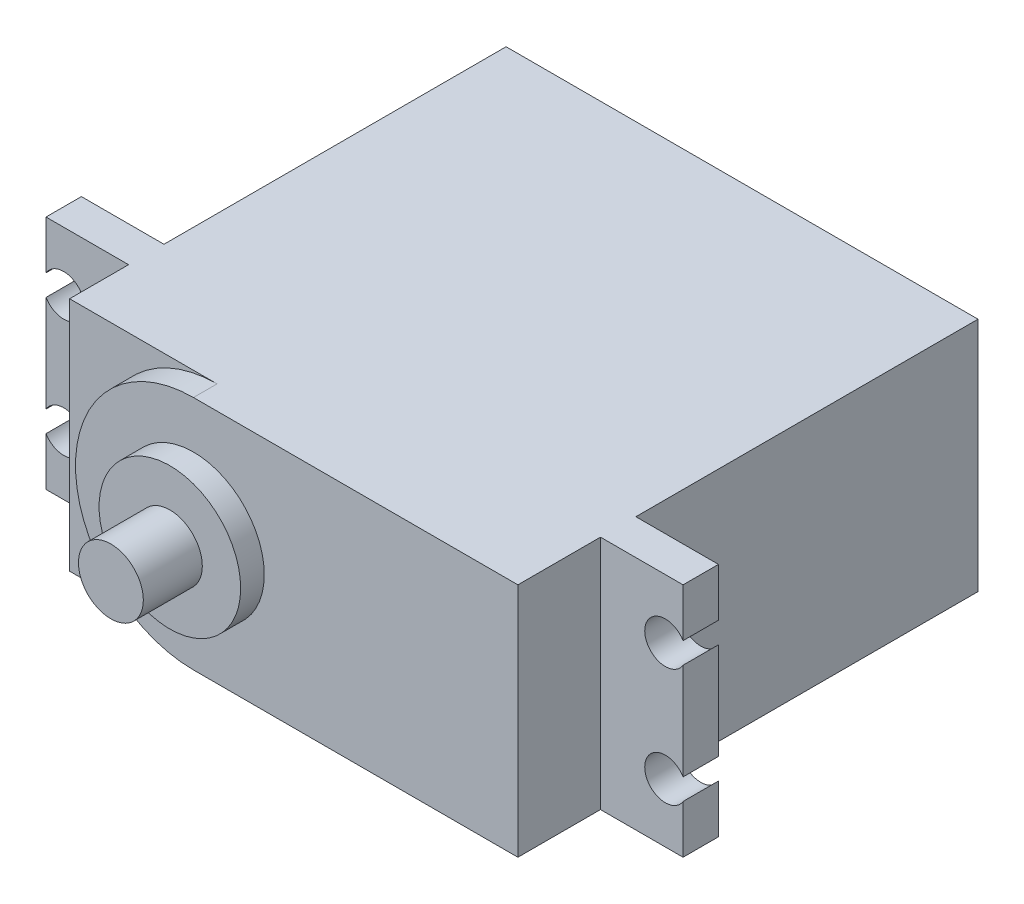
SolidWorks part; units mm, degrees
ref_plane "Front Plane" through (0, 0, 0) normal (0, 0, 1) x (1, 0, 0)
ref_plane "Top Plane" through (0, 0, 0) normal (0, 1, 0) x (1, 0, 0)
ref_plane "Right Plane" through (0, 0, 0) normal (1, 0, 0) x (0, 0, -1)
sketch "Sketch1" plane through (0, 0, 0) normal (0, 0, 1) x (1, 0, 0)
  line L1 (-20, -10) -> (20, -10)
  line L2 (-20, -10) -> (-20, 10)
  line L3 (-20, 10) -> (20, 10)
  line L4 (20, -10) -> (20, 10)
  line L5 (-20, -10) -> (20, 10) construction
  line L6 (-20, 10) -> (20, -10) construction
  point P0 (0, 0)
  dimension "D1" = 40
  dimension "D2" = 20
extrude "Boss-Extrude1" add sketch "Sketch1" along normal blind 37
sketch "Sketch2" plane through (0, 0, 37) normal (0, 0, 1) x (1, 0, 0)
  line L0 (-20, 10) -> (-20, -10) construction
  line L1 (-7.5, 10) -> (20, 10)
  line L2 (20, 10) -> (20, -10)
  line L3 (20, -10) -> (-7.5, -10)
  arc A0 (-7.5, 10) -> (-7.5, -10) centre (-7.5, 0) ccw
  dimension "D1" = 12.5
  dimension "D2" = 20
extrude "Boss-Extrude2" add sketch "Sketch2" along normal blind 2
sketch "Sketch3" plane through (0, 0, 39) normal (0, 0, 1) x (1, 0, 0)
  circle A0 centre (-7.5, 0) radius 6
  dimension "D1" = 12
extrude "Boss-Extrude3" add sketch "Sketch3" along normal blind 2
sketch "Sketch4" plane through (0, 0, 41) normal (0, 0, 1) x (1, 0, 0)
  circle A0 centre (-7.5, 0) radius 2.75
  dimension "D1" = 5.5
extrude "Boss-Extrude4" add sketch "Sketch4" along normal blind 5
ref_plane "Plane1" through (0, 0, 32) normal (0, 0, 1) x (1, 0, 0)
sketch "Sketch5" plane through (0, 0, 32) normal (0, 0, 1) x (1, 0, 0)
  line L0 (-27, 0) -> (-20, 0) construction
  line L1 (-20, -10) -> (-27, -10)
  line L2 (-20, -10) -> (-20, 10)
  line L3 (-20, 10) -> (-27, 10)
  line L4 (-27, -10) -> (-27, 10)
  line L6 (0, 23.4027) -> (0, -21.6577) construction
  line L8 (27, 0) -> (20, 0) construction
  line L9 (27, -10) -> (27, 10)
  line L10 (20, 10) -> (27, 10)
  line L11 (20, -10) -> (20, 10)
  line L12 (20, -10) -> (27, -10)
  dimension "D1" = 7
extrude "Boss-Extrude5" add sketch "Sketch5" against normal blind 3
sketch "Sketch7" plane through (0, 0, 32) normal (0, 0, 1) x (1, 0, 0)
  line L0 (-27, 0) -> (27, 0) construction
  line L1 (-27, 10) -> (-27, -10) construction
  line L2 (27, -10) -> (27, 10) construction
  line L3 (0, 16.2222) -> (0, -17.2054) construction
  circle A0 centre (-25.5, 5) radius 1.75
  circle A4 centre (-25.5, -5) radius 1.75
  circle A5 centre (25.5, -5) radius 1.75
  circle A6 centre (25.5, 5) radius 1.75
  dimension "D2" = 3.5
  dimension "D1" = 5
  dimension "D3" = 1.5
extrude "Cut-Extrude3" cut sketch "Sketch7" against normal through all
